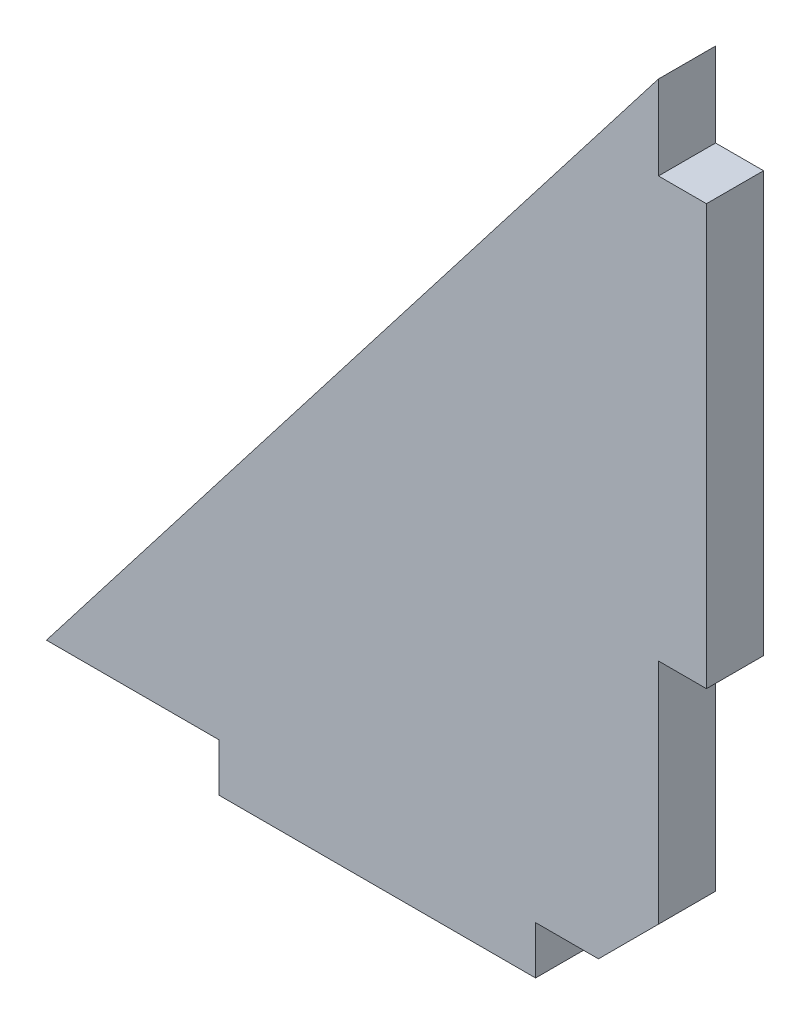
SolidWorks part; units mm, degrees
material "AISI 304"
ref_plane "Plano frontal" through (0, 0, 0) normal (0, 0, 1) x (1, 0, 0)
ref_plane "Plano superior" through (0, 0, 0) normal (0, 1, 0) x (1, 0, 0)
ref_plane "Plano direito" through (0, 0, 0) normal (1, 0, 0) x (0, 0, -1)
sketch "Esboço1" plane through (0, 0, 0) normal (0, 0, 1) x (1, 0, 0)
  line L0 (0, 0) -> (0, -7)
  line L1 (0, -7) -> (4, -7)
  line L2 (4, -7) -> (4, -42)
  line L3 (4, -42) -> (0, -42)
  line L4 (0, -42) -> (0, -61)
  line L5 (0, -61) -> (-5, -66)
  line L6 (-5, -66) -> (-10.24, -66)
  line L7 (-10.24, -66) -> (-10.24, -70)
  line L8 (-10.24, -70) -> (-36.64, -70)
  line L9 (-36.64, -70) -> (-36.64, -66)
  line L10 (-36.64, -66) -> (-51, -66)
  line L11 (-51, -66) -> (0, 0)
  point P3 (-50.155, -40.5721)
  point P14 (0, -41.6408)
  point P15 (0, -14.7901)
  point P16 (0, -34.3424)
  point P17 (0, -38.1246)
  point P20 (2.6095, 0.735)
  dimension "D1" = 4
  dimension "D2" = 4
  dimension "D3" = 10.24
  dimension "D4" = 26.4
  dimension "D5" = 70
  dimension "D6" = 51
  dimension "D7" = 4
  dimension "D8" = 5
  dimension "D9" = 135
  dimension "D10" = 24
  dimension "D11" = 35
extrude "Ressalto-extrusão1" add sketch "Esboço1" along normal blind 4.76
